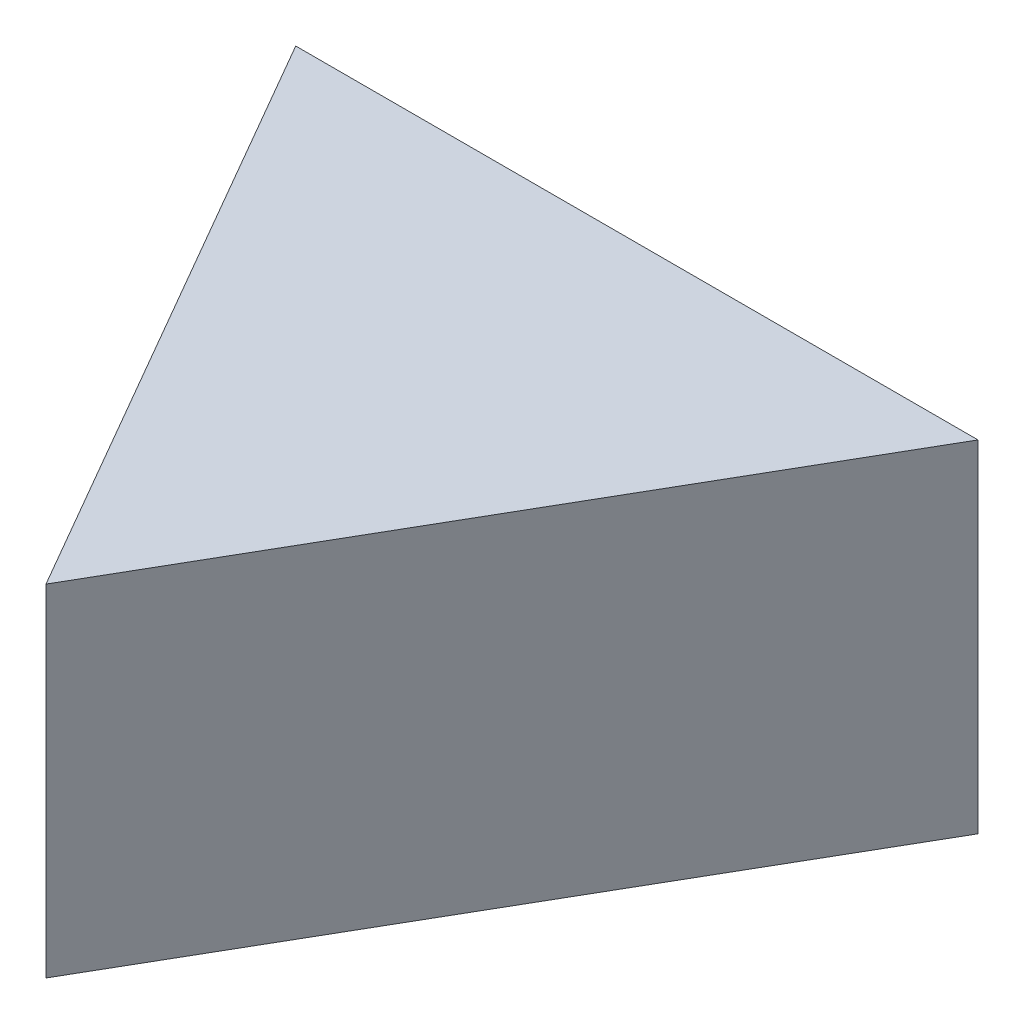
SolidWorks part; units mm, degrees
ref_plane "Přední rovina" through (0, 0, 0) normal (0, 0, 1) x (1, 0, 0)
ref_plane "Horní rovina" through (0, 0, 0) normal (0, 1, 0) x (1, 0, 0)
ref_plane "Pravá rovina" through (0, 0, 0) normal (1, 0, 0) x (0, 0, -1)
sketch "Sketch1" plane through (0, 0, 0) normal (0, 1, 0) x (1, 0, 0)
  line L0 (-20, 0) -> (20, 0)
  line L1 (20, 0) -> (0, -34.641)
  line L2 (0, -34.641) -> (0, 0) construction
  line L3 (-20, 0) -> (0, -34.641)
  dimension "D1" = 60
  dimension "D2" = 20
extrude "Boss-Extrude1" add sketch "Sketch1" along normal blind 20
